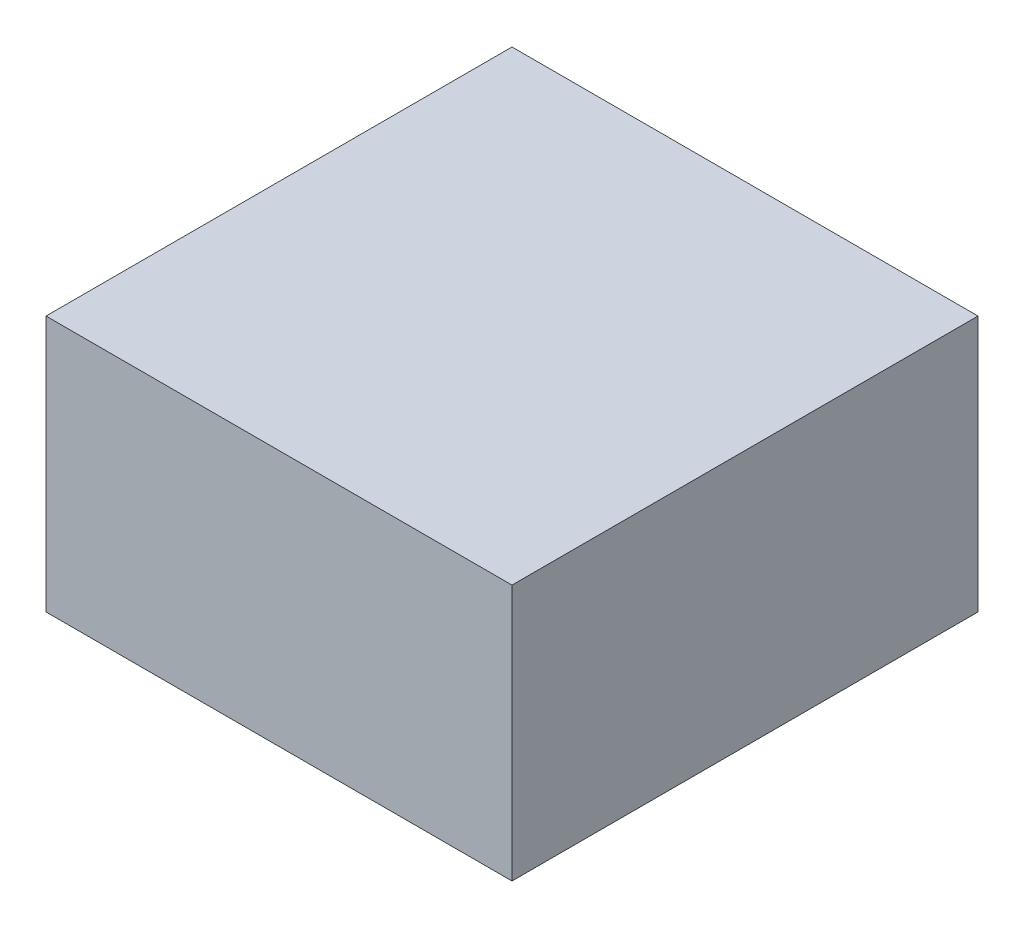
SolidWorks part; units mm, degrees
ref_plane "Front Plane" through (0, 0, 0) normal (0, 0, 1) x (1, 0, 0)
ref_plane "Top Plane" through (0, 0, 0) normal (0, 1, 0) x (1, 0, 0)
ref_plane "Right Plane" through (0, 0, 0) normal (1, 0, 0) x (0, 0, -1)
sketch "Sketch1" plane through (0, 0, 0) normal (0, 1, 0) x (1, 0, 0)
  line L1 (-5, 5) -> (5, 5)
  line L2 (-5, 5) -> (-5, -5)
  line L3 (-5, -5) -> (5, -5)
  line L4 (5, 5) -> (5, -5)
  line L5 (-5, 5) -> (5, -5) construction
  line L6 (-5, -5) -> (5, 5) construction
  point P0 (0, 0)
  dimension "D1" = 10
  dimension "D2" = 10
extrude "Boss-Extrude1" add sketch "Sketch1" along normal blind 5.5
